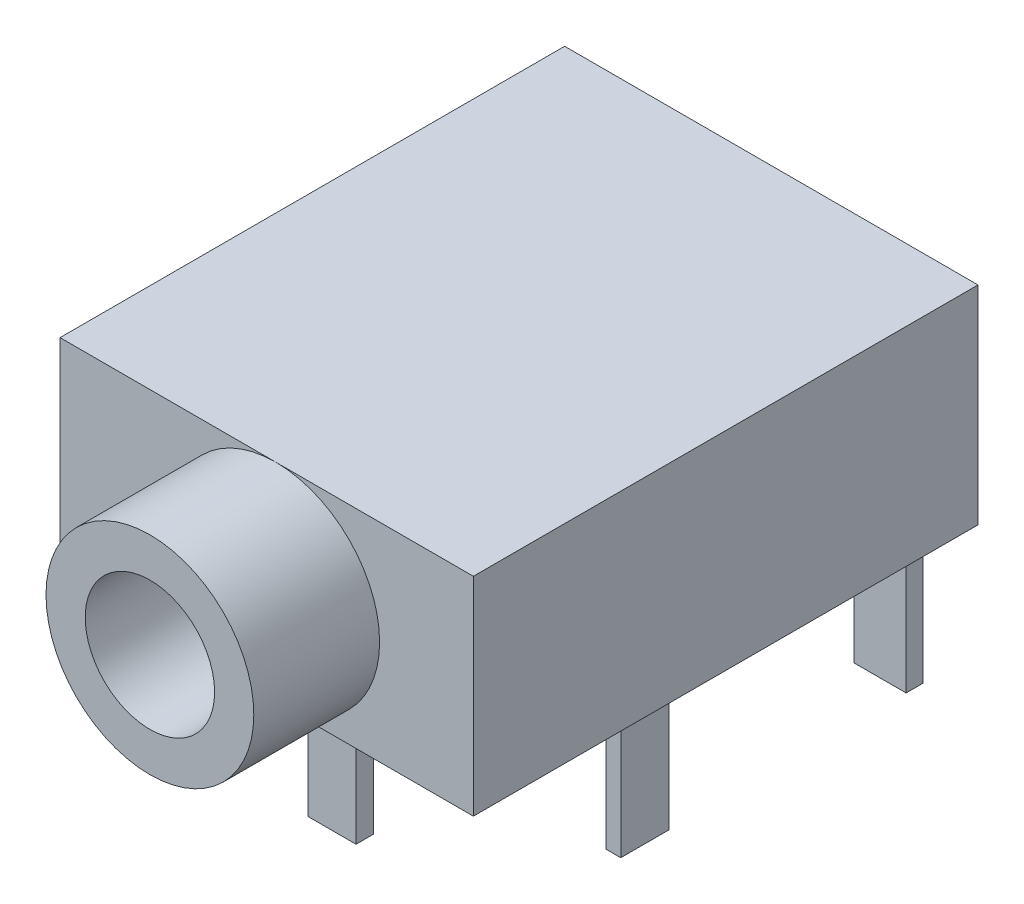
SolidWorks part; units mm, degrees
ref_plane "Front" through (0, 0, 0) normal (0, 0, 1) x (1, 0, 0)
ref_plane "Top" through (0, 0, 0) normal (0, 1, 0) x (1, 0, 0)
ref_plane "Right" through (0, 0, 0) normal (1, 0, 0) x (0, 0, -1)
sketch "Эскиз1" plane through (0, 0, 0) normal (1, 0, 0) x (0, 0, -1)
  line L0 (-3.5529, 13.6603) -> (14.0471, 13.6603) construction
  line L1 (0.0116, 5.7751) -> (0.0116, -0.006)
  line L2 (0.0116, -0.006) -> (14.0506, -0.006)
  line L3 (14.0506, -0.006) -> (14.0506, 5.7751)
  line L4 (14.0506, 5.7751) -> (0.0116, 5.7751)
  dimension "D1" = 17.6
extrude "Бобышка-Вытянуть1" add sketch "Эскиз1" along normal mid plane 11.5
sketch "Эскиз2" plane through (0, 0, -0.0116) normal (0, 0, 1) x (1, 0, 0)
  line L0 (-5.75, 5.7751) -> (-5.75, -0.006) construction
  line L1 (5.75, 5.7751) -> (-5.75, 5.7751) construction
  circle A0 centre (0.25, 2.8846) radius 2.8905
  circle A1 centre (0.25, 2.8846) radius 1.8
  point P5 (-5.75, 2.8846)
  dimension "D1" = 3.6
  dimension "D2" = 6
extrude "Бобышка-Вытянуть2" add sketch "Эскиз2" along normal blind 3.5
sketch "Эскиз3" plane through (0, -0.006, 0) normal (0, -1, 0) x (1, 0, 0)
  line L0 (11.6893, -2.4377) -> (20.8893, -2.4377) construction
  line L42 (4.8005, -13.4693) -> (3.3549, -13.4693)
  line L43 (4.8005, -13.0001) -> (4.8005, -13.4693)
  line L44 (4.8005, -13.0001) -> (3.3549, -13.0001)
  line L45 (-5.0656, -9.2995) -> (-5.0656, -10.7122)
  line L46 (-4.6256, -10.7122) -> (-5.0656, -10.7122)
  line L47 (-4.6256, -9.2995) -> (-4.6256, -10.7122)
  line L48 (-4.6256, -9.2995) -> (-5.0656, -9.2995)
  line L49 (-2.6338, -8.0257) -> (-2.6338, -9.4616)
  line L50 (-2.1706, -9.4616) -> (-2.6338, -9.4616)
  line L51 (-2.1706, -8.0257) -> (-2.1706, -9.4616)
  line L52 (-2.1706, -8.0257) -> (-2.6338, -8.0257)
  line L53 (4.3836, -5.0612) -> (4.3836, -6.4045)
  line L54 (4.8005, -6.4045) -> (4.3836, -6.4045)
  line L55 (4.8005, -5.0612) -> (4.8005, -6.4045)
  line L56 (4.8005, -5.0612) -> (4.3836, -5.0612)
  line L57 (-0.5494, -1.7031) -> (-0.5494, -2.1894)
  line L58 (0.7938, -2.1894) -> (-0.5494, -2.1894)
  line L59 (0.7938, -1.7031) -> (0.7938, -2.1894)
  line L60 (0.7938, -1.7031) -> (-0.5494, -1.7031)
  line L61 (3.3549, -13.0001) -> (3.3549, -13.4693)
  dimension "D1" = 9.2
extrude "Бобышка-Вытянуть3" add sketch "Эскиз3" along normal blind 4
